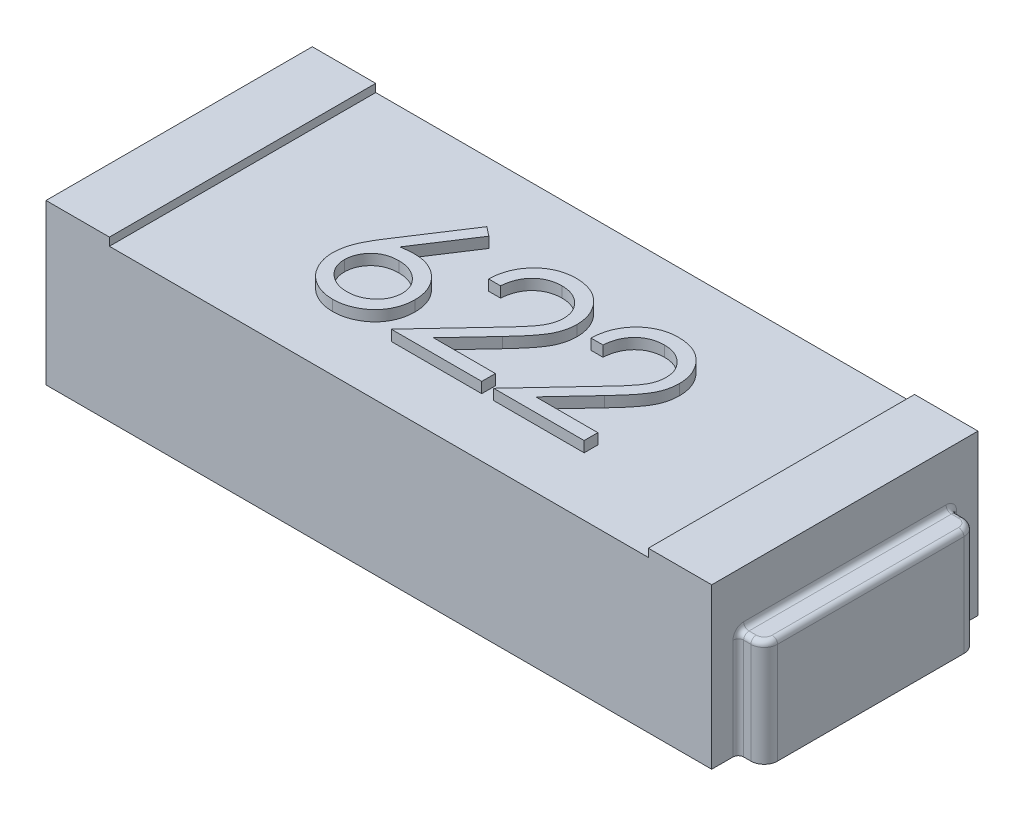
SolidWorks part; units mm, degrees
ref_plane "Plan de face" through (0, 0, 0) normal (0, 0, 1) x (1, 0, 0)
ref_plane "Plan de dessus" through (0, 0, 0) normal (0, 1, 0) x (1, 0, 0)
ref_plane "Plan de droite" through (0, 0, 0) normal (1, 0, 0) x (0, 0, -1)
sketch "Esquisse1" plane through (0, 0, 0) normal (0, 1, 0) x (1, 0, 0)
  line L1 (1.25, -0.5) -> (-1.25, -0.5)
  line L2 (1.25, -0.5) -> (1.25, 0.5)
  line L3 (1.25, 0.5) -> (-1.25, 0.5)
  line L4 (-1.25, -0.5) -> (-1.25, 0.5)
  line L5 (1.25, -0.5) -> (-1.25, 0.5) construction
  line L6 (1.25, 0.5) -> (-1.25, -0.5) construction
  point P0 (0, 0)
  dimension "D1" = 2.5
  dimension "D2" = 1
extrude "Boss.-Extru.1" add sketch "Esquisse1" along normal blind 0.6
sketch "Esquisse2" plane through (0, 0.6, 0) normal (0, 1, 0) x (1, 0, 0)
  line L0 (1.25, 0.5) -> (-1.25, 0.5) construction
  line L1 (1.0118, -0.5) -> (-1.0118, -0.5)
  line L2 (1.0118, -0.5) -> (1.0118, 0.5)
  line L3 (1.0118, 0.5) -> (-1.0118, 0.5)
  line L4 (-1.0118, -0.5) -> (-1.0118, 0.5)
  line L5 (1.0118, -0.5) -> (-1.0118, 0.5) construction
  line L6 (1.0118, 0.5) -> (-1.0118, -0.5) construction
  point P0 (0, 0)
extrude "Enlèv. mat.-Extru.1" cut sketch "Esquisse2" against normal blind 0.03
sketch "Esquisse3" plane through (0, 0, 0) normal (0, 1, 0) x (1, 0, 0)
  line L0 (1.25, -0.5) -> (1.25, 0.5) construction
  line L1 (1.25, 0.4) -> (1.2971, 0.4)
  line L2 (1.25, 0.4) -> (1.25, -0.4)
  line L3 (1.25, -0.4) -> (1.2971, -0.4)
  line L4 (1.3471, 0.35) -> (1.3471, -0.35)
  line L5 (1.25, 0.5) -> (1.0118, 0.5) construction
  line L6 (1.0118, -0.5) -> (1.25, -0.5) construction
  arc A0 (1.2971, -0.4) -> (1.3471, -0.35) centre (1.2971, -0.35) ccw
  arc A1 (1.2971, 0.4) -> (1.3471, 0.35) centre (1.2971, 0.35) cw
  dimension "D1" = 0.05
  dimension "D2" = 0.1
  dimension "D3" = 0.1
extrude "Boss.-Extru.2" add sketch "Esquisse3" along normal blind 0.4
fillet "Congé1" radius 0.02 8 edges at (1.25, 0.2, -0.4) (1.25, 0.2, 0.4) (1.2736, 0.4, -0.4) (1.3325, 0.4, -0.3854) (1.3471, 0.4, 0) (1.3325, 0.4, 0.3854) (1.2736, 0.4, 0.4) (1.25, 0.4, 0)
mirror "Symétrie2" about plane through (0, 0, 0) normal (1, 0, 0) of "Congé1", "Boss.-Extru.2"
sketch "Esquisse4" plane through (0, 0.57, 0) normal (0, 1, 0) x (1, 0, 0)
  line L0 (0.7576, -0.2803) -> (-0.7576, -0.2803) construction
  text T0 "622\r\n" font "Century Gothic" height 0.5
  point P3 (0, -0.2803)
extrude "Boss.-Extru.3" add sketch "Esquisse4" along normal blind 0.04
